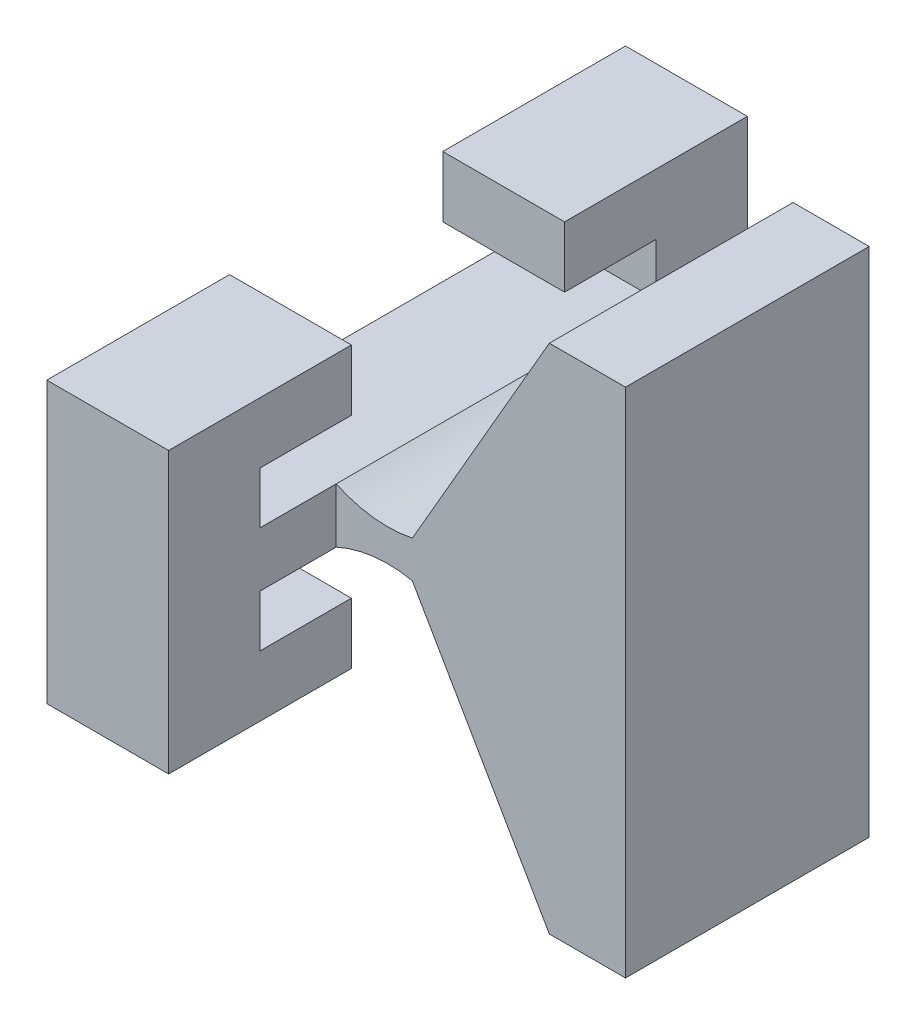
SolidWorks part; units mm, degrees
material "Резина"
ref_plane "Plane1" through (0, 0, 0) normal (0, 0, 1) x (1, 0, 0)
ref_plane "Plane2" through (0, 0, 0) normal (0, 1, 0) x (1, 0, 0)
ref_plane "Plane3" through (0, 0, 0) normal (1, 0, 0) x (0, 0, -1)
sketch "Эскиз2" plane through (0, 0, 0) normal (0, 0, 1) x (1, 0, 0)
  line L0 (0, 0) -> (0, 0.9)
  line L1 (0, 0.9) -> (4, 0.9)
  line L2 (0, 0) -> (34.0426, 0) construction
  line L3 (13.5, 8.4) -> (13.5, -8.4)
  line L4 (11, 8.4) -> (6.5, 0.6058)
  line L5 (11, 8.4) -> (13.5, 8.4)
  line L6 (0, 0) -> (0, -0.9)
  line L7 (0, -0.9) -> (4, -0.9)
  line L8 (11, -8.4) -> (6.5, -0.6058)
  line L9 (11, -8.4) -> (13.5, -8.4)
  arc A0 (6.5, 0.6058) -> (4, 0.9) centre (5.6938, 4.5237) cw
  arc A1 (6.5, -0.6058) -> (4, -0.9) centre (5.6938, -4.5237) ccw
  point P18 (13.5, 0)
  dimension "D1" = 4
  dimension "D2" = 4
  dimension "D3" = 16.8
  dimension "D4" = 2.5
  dimension "D5" = 9
  dimension "D6" = 60
  dimension "D7" = 7
  dimension "D8" = 1.8
  dimension "D9" = 9.5
extrude "Бобышка-Вытянуть1" add sketch "Эскиз2" along normal mid plane 8
sketch "Эскиз3" plane through (0, 0, -4) normal (0, 0, -1) x (-1, 0, 0)
  line L1 (0, -0.9) -> (-4, -0.9)
  line L2 (0, -0.9) -> (0, 0.9)
  line L3 (0, 0.9) -> (-4, 0.9)
  line L4 (-4, -0.9) -> (-4, 0.9)
extrude "Бобышка-Вытянуть2" add sketch "Эскиз3" along normal blind 5.5
mirror "Зеркальное отражение1" about plane through (0, 0, 0) normal (0, 0, 1) of "Бобышка-Вытянуть2"
sketch "Эскиз5" plane through (0, 0.9, 0) normal (0, 1, 0) x (1, 0, 0)
  line L0 (0, 9.5) -> (4, 9.5)
  line L1 (0, 9.5) -> (0, 6.5)
  line L2 (4, 9.5) -> (4, 6.5)
  line L3 (0, 6.5) -> (4, 6.5)
  dimension "D1" = 3
extrude "Бобышка-Вытянуть3" add sketch "Эскиз5" along normal blind 3.7
mirror "Зеркальное отражение2" about plane through (0, 0, 0) normal (0, 0, 1) of "Бобышка-Вытянуть3"
mirror "Зеркальное отражение3" about plane through (0, 0, 0) normal (0, 1, 0) of "Зеркальное отражение2", "Бобышка-Вытянуть3"
sketch "Эскиз7" plane through (0, 0, 6.5) normal (0, 0, -1) x (-1, 0, 0)
  line L0 (0, -4.6) -> (0, 4.6) construction
  line L1 (-4, 4.6) -> (0, 4.6)
  line L2 (-4, 4.6) -> (-4, 2.6)
  line L3 (-4, 2.6) -> (0, 2.6)
  line L4 (0, 4.6) -> (0, 2.6)
  dimension "D1" = 2
extrude "Бобышка-Вытянуть4" add sketch "Эскиз7" along normal blind 3
mirror "Зеркальное отражение4" about plane through (0, 0, 0) normal (0, 0, 1) of "Бобышка-Вытянуть4"
mirror "Зеркальное отражение5" about plane through (0, 0, 0) normal (0, 1, 0) of "Зеркальное отражение4", "Бобышка-Вытянуть4"
